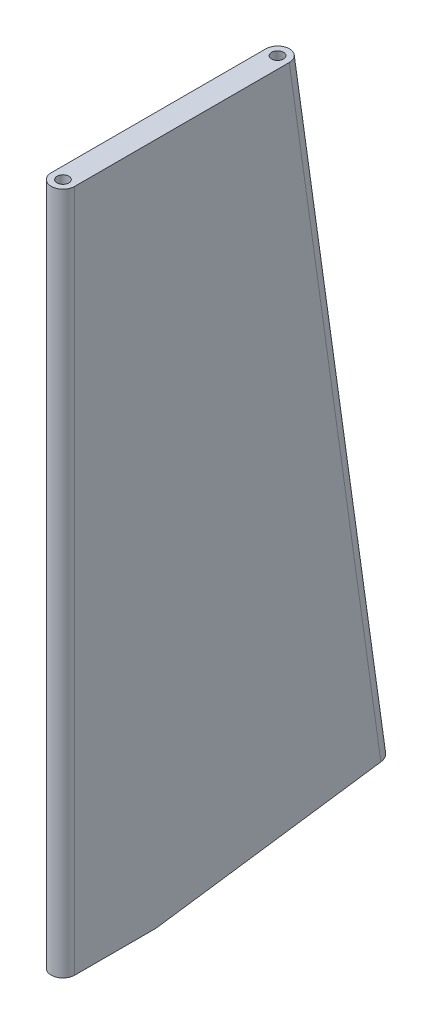
SolidWorks part; units mm, degrees
ref_plane "Спереди" through (0, 0, 0) normal (0, 0, 1) x (1, 0, 0)
ref_plane "Сверху" through (0, 0, 0) normal (0, 1, 0) x (1, 0, 0)
ref_plane "Справа" through (0, 0, 0) normal (1, 0, 0) x (0, 0, -1)
sketch "Эскиз1" plane through (0, 0, 0) normal (1, 0, 0) x (0, 0, -1)
  line L0 (0, 58) -> (16.2063, 58)
  line L1 (16.2063, 58) -> (24, 2.545)
  line L2 (24, 2.545) -> (5.8915, 0)
  line L3 (5.8915, 0) -> (0, 0)
  line L4 (0, 0) -> (0, 58)
  line L5 (0, 50) -> (0, -50) construction
  line L6 (50, 0) -> (-50, 0) construction
  dimension "D1" = 24
  dimension "D2" = 82
  dimension "D3" = 90
  dimension "D4" = 58
  dimension "D5" = 56
extrude "Бобышка-Вытянуть1" add sketch "Эскиз1" along normal blind 2 contours L1 L2 L3 L4 L0
sketch "Эскиз2" plane through (0, 0, 0) normal (0, 1, 0) x (1, 0, 0)
  line L0 (2, 0) -> (0, 0)
  line L1 (0, 0) -> (0, -1)
  line L2 (2, 0) -> (2, -1)
  circle A0 centre (1, -1) radius 0.5
  arc A1 (2, -1) -> (0, -1) centre (1, -1) cw
  point P7 (1, 0)
  dimension "D1" = 1
  dimension "D2" = 1
extrude "Бобышка-Вытянуть2" add sketch "Эскиз2" along normal up to surface (58 mm away) up to face at (1, 58, -8.1032)
sketch "Эскиз3" plane through (0, -0.812, -0.1141) normal (0, -0.9903, -0.1392) x (1, 0, 0)
  line L0 (0, -25.1206) -> (0, -24.1206)
  line L1 (0, -24.1206) -> (2, -24.1206)
  line L2 (2, -24.1206) -> (2, -25.1206)
  circle A0 centre (1, -25.1206) radius 0.5
  arc A1 (2, -25.1206) -> (0, -25.1206) centre (1, -25.1206) cw
  point P9 (1, -24.1206)
  dimension "D1" = 1
  dimension "D2" = 1
extrude "Бобышка-Вытянуть3" add sketch "Эскиз3" against normal up to surface (55.7892 mm away)
